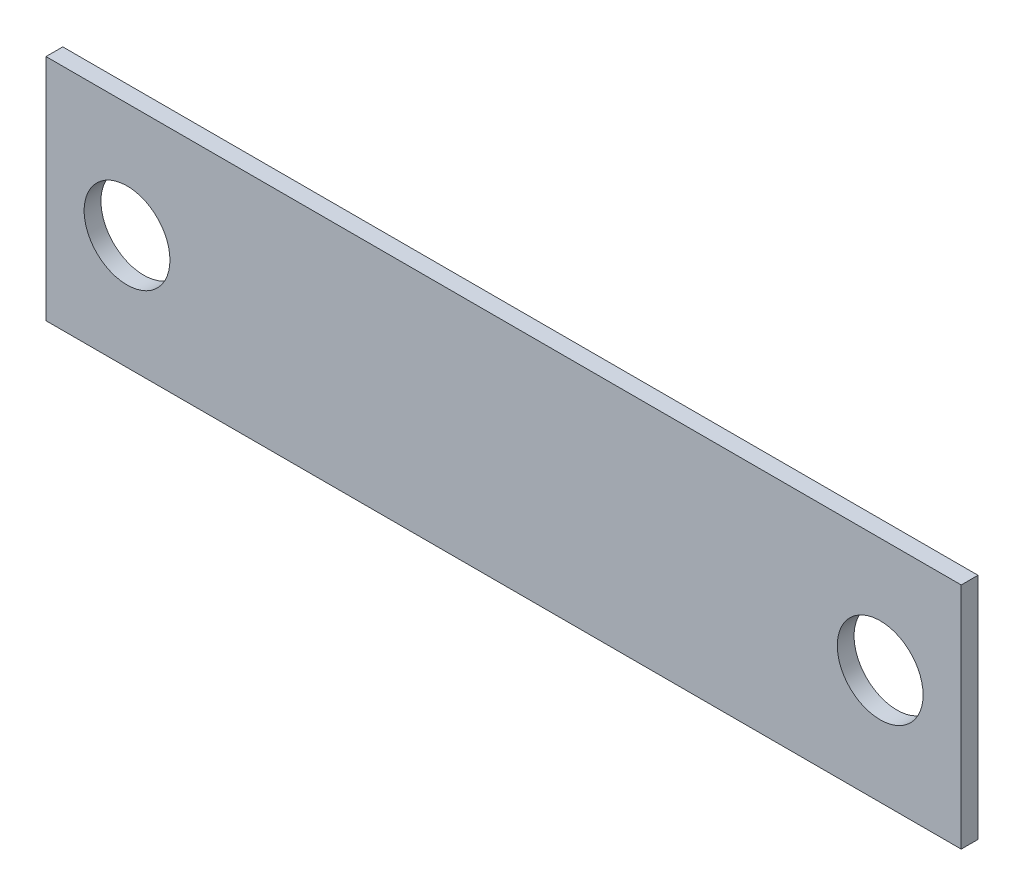
SolidWorks part; units mm, degrees
ref_plane "Front Plane" through (0, 0, 0) normal (0, 0, 1) x (1, 0, 0)
ref_plane "Top Plane" through (0, 0, 0) normal (0, 1, 0) x (1, 0, 0)
ref_plane "Right Plane" through (0, 0, 0) normal (1, 0, 0) x (0, 0, -1)
sketch "Sketch1" plane through (0, 0, 0) normal (0, 0, 1) x (1, 0, 0)
  line L1 (-152.4, -38.1) -> (152.4, -38.1)
  line L2 (-152.4, -38.1) -> (-152.4, 38.1)
  line L3 (-152.4, 38.1) -> (152.4, 38.1)
  line L4 (152.4, -38.1) -> (152.4, 38.1)
  line L5 (-152.4, -38.1) -> (152.4, 38.1) construction
  line L6 (-152.4, 38.1) -> (152.4, -38.1) construction
  point P0 (0, 0)
  dimension "D1" = 304.8
  dimension "D2" = 76.2
extrude "Boss-Extrude1" add sketch "Sketch1" along normal blind 5.588
sketch "Sketch2" plane through (0, 0, 5.588) normal (0, 0, 1) x (1, 0, 0)
  line L0 (-125.4125, 0) -> (125.4125, 0) construction
  line L2 (-139.7, 38.1) -> (-139.7, -38.1) construction
  line L3 (152.4, 38.1) -> (-152.4, 38.1) construction
  line L4 (-152.4, -38.1) -> (152.4, -38.1) construction
  line L5 (-152.4, 38.1) -> (-152.4, -38.1) construction
  circle A0 centre (-125.4125, 0) radius 14.2875
  circle A1 centre (125.4125, 0) radius 14.2875
  point P4 (0, 0)
  dimension "D1" = 28.575
  dimension "D2" = 12.7
extrude "Cut-Extrude1" cut sketch "Sketch2" against normal through all
